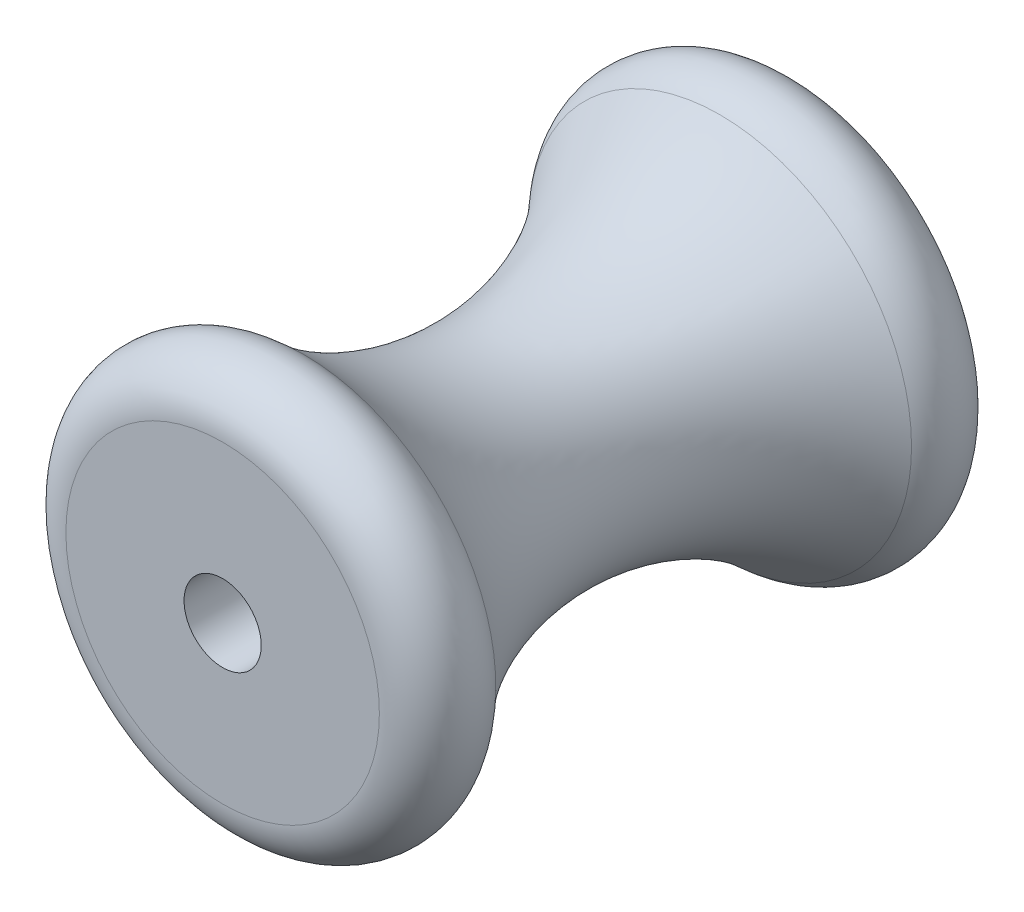
SolidWorks part; units mm, degrees
ref_plane "Front Plane" through (0, 0, 0) normal (0, 0, 1) x (1, 0, 0)
ref_plane "Top Plane" through (0, 0, 0) normal (0, 1, 0) x (1, 0, 0)
ref_plane "Right Plane" through (0, 0, 0) normal (1, 0, 0) x (0, 0, -1)
sketch "Sketch1" plane through (0, 0, 0) normal (1, 0, 0) x (0, 0, -1)
  line L0 (12.5, 0) -> (-12.5, 0) construction
  line L2 (12.5, 1.6) -> (-12.5, 1.6) construction
  line L4 (0, 9.35) -> (0, -9.35) construction
  line L5 (12.5, 1.6) -> (12.5, 17) construction
  line L6 (-12.5, 1.6) -> (-12.5, 17) construction
  line L7 (12, 1.6) -> (12, 13.5)
  line L8 (-12, 1.6) -> (-12, 13.5)
  line L9 (12, 1.6) -> (-12, 1.6)
  line L10 (12.5, -16.8891) -> (12.5, 17.4787) construction
  circle A0 centre (0, 17) radius 12.5 construction
  arc A1 (12, 13.5) -> (-12, 13.5) centre (0, 17) cw
  point P2 (0, 0)
  dimension "D1" = 1
revolve "Revolve1" add sketch "Sketch1" angle 360 about L0
fillet "Fillet1" radius 2 2 edges at (0, 13.5, 12) (0, 13.5, -12)
